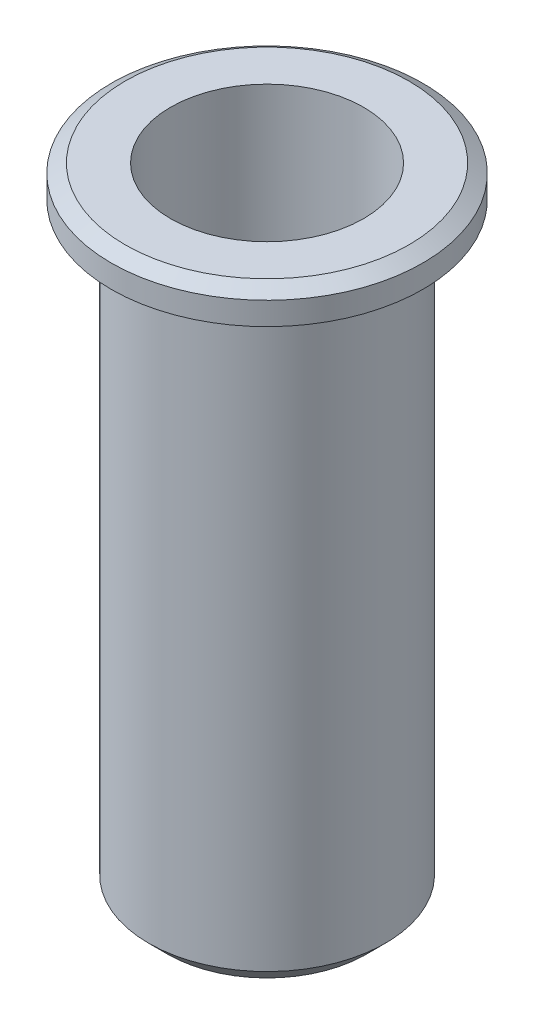
SolidWorks part; units mm, degrees
ref_plane "Front Plane" through (0, 0, 0) normal (0, 0, 1) x (1, 0, 0)
ref_plane "Top Plane" through (0, 0, 0) normal (0, 1, 0) x (1, 0, 0)
ref_plane "Right Plane" through (0, 0, 0) normal (1, 0, 0) x (0, 0, -1)
sketch "Sketch1" plane through (0, 0, 0) normal (0, 0, 1) x (1, 0, 0)
  line L0 (0, 25.1479) -> (0, 0) construction
  line L2 (2.2987, 0) -> (3.988, 0)
  line L3 (3.988, 0) -> (4.75, 0.762)
  line L4 (4.75, 0.762) -> (4.75, 24.2316)
  line L5 (4.75, 24.2316) -> (6.25, 24.2316)
  line L6 (6.25, 24.2316) -> (6.25, 25.1479)
  line L7 (6.25, 25.1479) -> (5.6929, 25.5016)
  line L8 (5.6929, 25.5016) -> (3.8735, 25.5016)
  line L9 (3.8735, 25.5016) -> (3.8735, 2.3652)
  line L10 (3.8735, 2.3652) -> (2.2987, 2.3652)
  line L11 (2.2987, 2.3652) -> (2.2987, 0)
  point P3 (1.9295, 0)
  point P14 (0.8069, 0)
  dimension "D1" = 25.5016
  dimension "D2" = 9.5
  dimension "D3" = 45
  dimension "D4" = 0.762
  dimension "D5" = 4.5974
  dimension "D6" = 1.27
  dimension "D7" = 12.5
  dimension "D8" = 7.747
revolve "Revolve1" add sketch "Sketch1" angle 360 about L0
